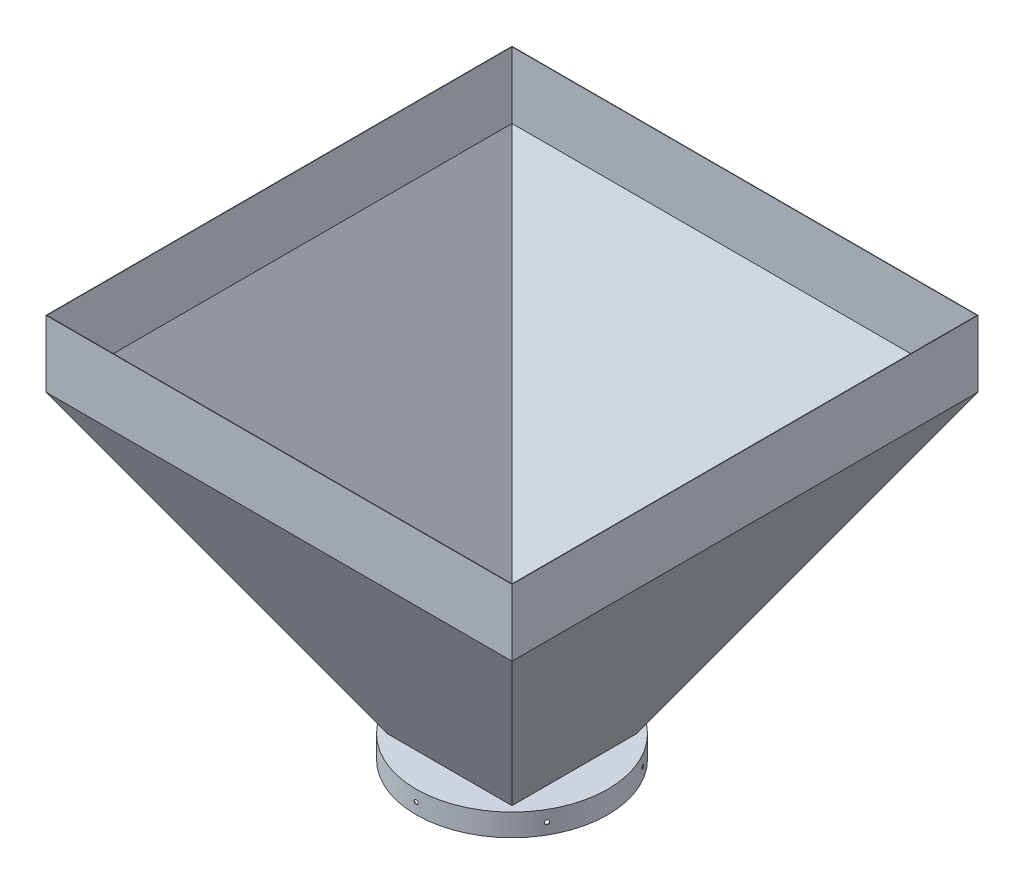
SolidWorks part; units mm, degrees
material "AISI 304"
ref_plane "Alzado" through (0, 0, 0) normal (0, 0, 1) x (1, 0, 0)
ref_plane "Planta" through (0, 0, 0) normal (0, 1, 0) x (1, 0, 0)
ref_plane "Vista lateral" through (0, 0, 0) normal (1, 0, 0) x (0, 0, -1)
sketch "Croquis1" plane through (0, 0, 0) normal (0, 1, 0) x (1, 0, 0)
  line L1 (-525, 525) -> (525, 525)
  line L2 (-525, 525) -> (-525, -525)
  line L3 (-525, -525) -> (525, -525)
  line L4 (525, 525) -> (525, -525)
  line L5 (-525, 525) -> (525, -525) construction
  line L6 (-525, -525) -> (525, 525) construction
  point P0 (0, 0)
  dimension "D1" = 1050
ref_plane "Plano1" through (0, -666.844, 0) normal (0, -1, 0) x (-1, 0, 0)
sketch "Croquis2" plane through (0, -666.844, 0) normal (0, -1, 0) x (-1, 0, 0)
  line L0 (525, 525) -> (-525, -525) construction
  line L1 (-140, -140) -> (140, -140)
  line L2 (-140, -140) -> (-140, 140)
  line L3 (-140, 140) -> (140, 140)
  line L4 (140, -140) -> (140, 140)
  line L5 (-140, -140) -> (140, 140) construction
  line L6 (-140, 140) -> (140, -140) construction
  point P0 (0, 0)
  dimension "D1" = 280
loft "Recubrir1" add profiles "Croquis1", "Croquis2"
sketch "Croquis3" plane through (0, 0, 0) normal (0, 1, 0) x (1, 0, 0)
  line L1 (-525, 525) -> (525, 525)
  line L2 (-525, 525) -> (-525, -525)
  line L3 (-525, -525) -> (525, -525)
  line L4 (525, 525) -> (525, -525)
extrude "Saliente-Extruir1" add sketch "Croquis3" along normal blind 150
sketch "Croquis4" plane through (0, -666.844, 0) normal (0, -1, 0) x (1, 0, 0)
  circle A0 centre (0, 0) radius 215.9
  dimension "D1" = 431.8
extrude "Saliente-Extruir2" add sketch "Croquis4" along normal blind 50 contours A0
shell "Vaciado1" thickness 1
ref_plane "Plano2" through (0, 0, -215.9) normal (0, 0, -1) x (-1, 0, 0)
hole_wizard "Taladro de margen para M81" positions "Croquis6" profile "Croquis7" hole size "M8" standard "ISO" end condition through all
sketch "Croquis6" plane through (0, 0, -215.9) normal (0, 0, -1) x (-1, 0, 0)
  line L0 (215.9, -666.844) -> (-215.9, -666.844) construction
  line L1 (-138.268, -667.844) -> (138.268, -667.844) construction
  point P0 (0, -691.844)
  point P7 (0, -667.844)
  dimension "D1" = 25
sketch "Croquis7" plane through (0, -691.844, -215.9) normal (1, 0, 0) x (0, 1, 0)
  line L0 (0, 0) -> (0, 933.0635)
  line L1 (0, 933.0635) -> (4.5, 933.0635)
  line L2 (4.5, 933.0635) -> (4.5, 0)
  line L5 (4.5, 0) -> (0, 0)
  line L11 (0, -6.35) -> (0, 107.95) construction
  dimension "Diámetro de taladro hasta el siguiente" = 9
  dimension "Profundidad de taladro hasta el siguiente" = 933.0635
pattern_circular "MatrizC1" count 6 every 60 about axis through (0, -716.844, 0) along (0, 1, 0) of "Taladro de margen para M81"
